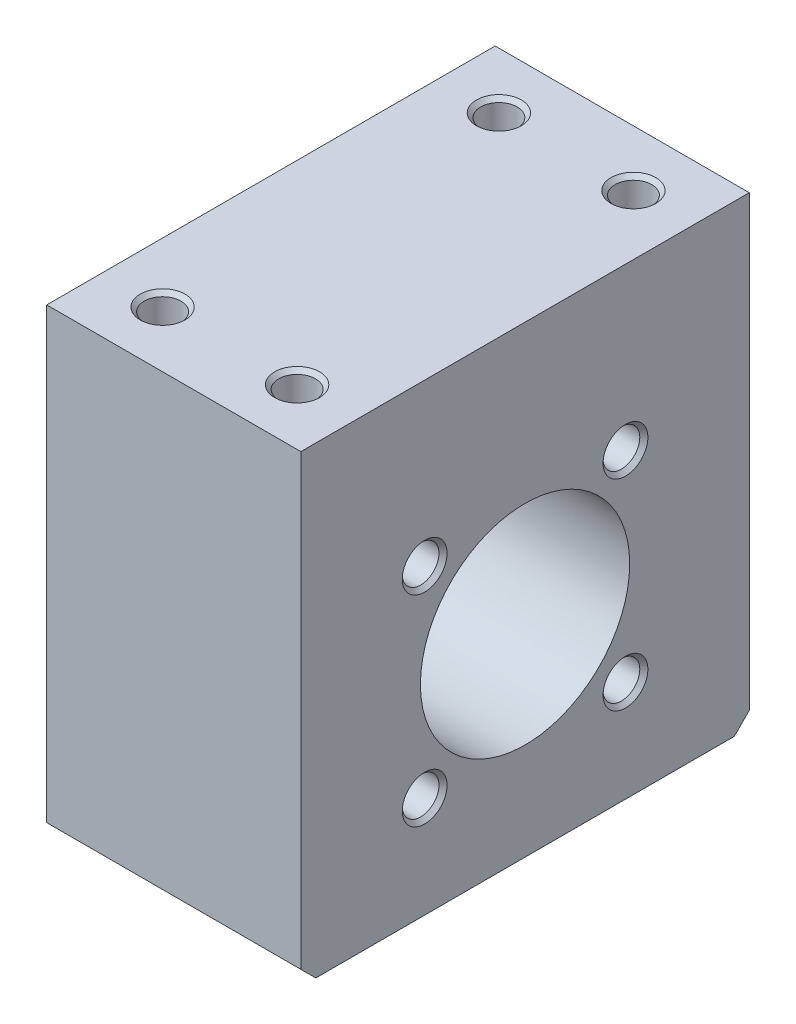
SolidWorks part; units mm, degrees
ref_plane "Piano frontale" through (0, 0, 0) normal (0, 0, 1) x (1, 0, 0)
ref_plane "Piano superiore" through (0, 0, 0) normal (0, 1, 0) x (1, 0, 0)
ref_plane "Piano destro" through (0, 0, 0) normal (1, 0, 0) x (0, 0, -1)
ref_plane "Piano1" through (17, 0, 0) normal (1, 0, 0) x (0, 0, -1)
sketch "Schizzo1" plane through (17, 0, 0) normal (1, 0, 0) x (0, 0, -1)
  line L0 (30, -27) -> (30, 35)
  line L1 (30, 35) -> (-30, 35)
  line L2 (-30, 35) -> (-30, -27)
  line L3 (-30, -27) -> (30, -27)
extrude "Estrusione-Estrusione1" add sketch "Schizzo1" against normal blind 34
hole_wizard "Foro per Vite M24-1" positions "Schizzo3" profile "Schizzo2" hole size "M24" standard "Ansi Metric"
sketch "Schizzo3" plane through (17, 0, 0) normal (1, 0, 0) x (0, 0, -1)
  point P0 (0, 0)
sketch "Schizzo2" plane through (17, 0, 0) normal (0, 1, 0) x (0, 0, -1)
  line L0 (0, 0) -> (0, 34)
  line L1 (0, 34) -> (14, 34)
  line L2 (14, 34) -> (14, 0)
  line L5 (14, 0) -> (0, 0)
  line L11 (0, -6.35) -> (0, 107.95) construction
  dimension "Thru Hole Dia." = 28
  dimension "Thru Hole Depth" = 34
hole_wizard "Foro1" positions "Schizzo5" profile "Schizzo4" legacy
sketch "Schizzo5" plane through (0, 35, 0) normal (0, 1, 0) x (1, 0, 0)
  point P0 (9, 22.5)
  point P1 (9, -22.5)
  point P2 (-9, 22.5)
  point P3 (-9, -22.5)
sketch "Schizzo4" plane through (9, 35, -22.5) normal (1, 0, 0) x (0, 0, 1)
  line L0 (0, 0) -> (0, 15.7321)
  line L1 (0, 15.7321) -> (2.4585, 14.3126)
  line L2 (2.4585, 14.3126) -> (2.4585, 0)
  line L4 (2.4585, 0) -> (0, 0)
  line L6 (0, 15.7321) -> (-2.4585, 14.3126) construction
  line L7 (0, -4.2442) -> (0, 117.3081) construction
  dimension "Diameter" = 4.917
  dimension "Depth" = 14.3126
  dimension "Drill Angle" = 120
hole_wizard "Foro2" positions "Schizzo7" profile "Schizzo6" legacy
sketch "Schizzo7" plane through (17, 0, 0) normal (1, 0, 0) x (0, 0, -1)
  point P0 (13.435, 13.435)
  point P1 (-13.435, -13.435)
  point P2 (13.435, -13.435)
  point P3 (-13.435, 13.435)
sketch "Schizzo6" plane through (17, 13.435, -13.435) normal (0, 1, 0) x (0, 0, -1)
  line L0 (0, 0) -> (0, 13.7321)
  line L1 (0, 13.7321) -> (2.4585, 12.3126)
  line L2 (2.4585, 12.3126) -> (2.4585, 0)
  line L4 (2.4585, 0) -> (0, 0)
  line L6 (0, 13.7321) -> (-2.4585, 12.3126) construction
  line L7 (0, -4.2442) -> (0, 117.3081) construction
  dimension "Diameter" = 4.917
  dimension "Depth" = 12.3126
  dimension "Drill Angle" = 120
chamfer "Smusso1" distance 0.5415 angle 45 8 edges at (-9, 35, 24.9585) (9, 35, 24.9585) (17, -13.435, 10.9765) (-9, 35, -20.0415) (17, -13.435, -15.8935) (17, 13.435, 10.9765) (17, 13.435, -15.8935) (9, 35, -20.0415)
chamfer "Smusso2" distance 2 angle 45 2 edges at (0, -27, 30) (0, -27, -30)
